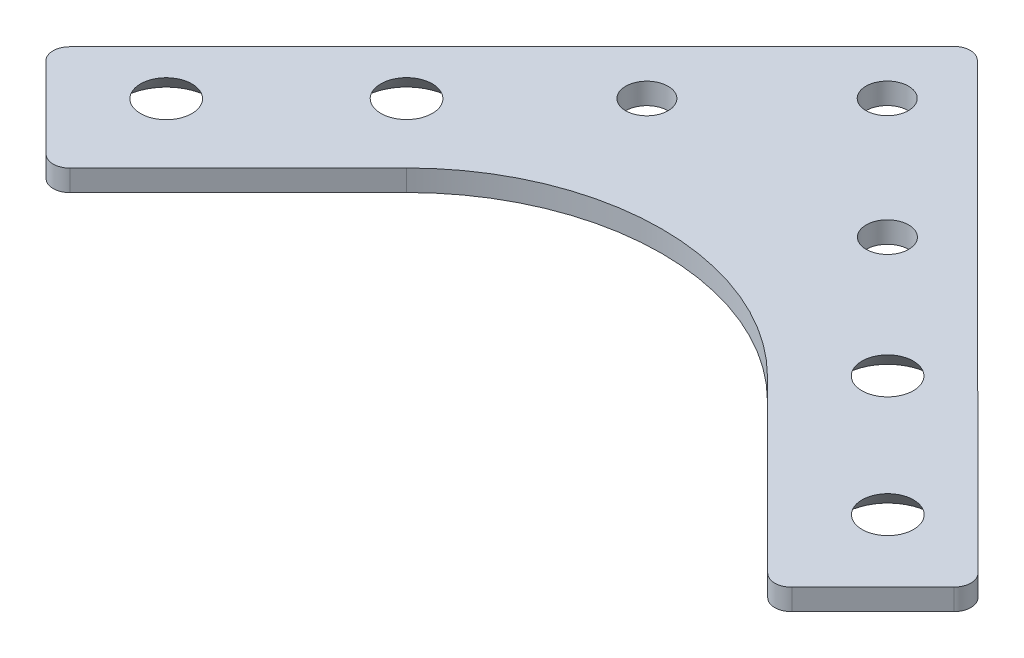
SolidWorks part; units mm, degrees
material "6061 Alloy"
ref_plane "Front Plane" through (0, 0, 0) normal (0, 0, 1) x (1, 0, 0)
ref_plane "Top Plane" through (0, 0, 0) normal (0, 1, 0) x (1, 0, 0)
ref_plane "Right Plane" through (0, 0, 0) normal (1, 0, 0) x (0, 0, -1)
sketch "Outline" plane through (0, 43.8334, 0) normal (0, -1, 0) x (1, 0, 0)
  line L0 (175.1714, -660.3981) -> (172.9281, -658.1513)
  line L1 (175.1714, -660.3981) -> (-309.3782, -175.0804) construction
  line L2 (172.9281, -658.1513) -> (175.175, -655.908)
  line L3 (176.9724, -654.1133) -> (243.4309, -587.7601)
  line L7 (227.7279, -572.0322) -> (202.162, -597.5577)
  line L8 (193.1461, -642.4518) -> (-291.4035, -157.1341) construction
  line L9 (148.2804, -597.515) -> (123.1556, -572.3504)
  line L12 (107.4278, -588.0534) -> (173.3803, -654.1105)
  line L16 (107.4306, -584.4613) -> (119.5635, -572.3475)
  line L18 (243.4337, -584.168) -> (231.32, -572.035)
  arc A0 (202.162, -597.5577) -> (148.2804, -597.515) centre (175.2425, -570.5956) cw
  arc A3 (176.9724, -654.1133) -> (173.3803, -654.1105) centre (175.1778, -652.3159) cw
  arc A4 (107.4306, -584.4613) -> (107.4278, -588.0534) centre (109.2252, -586.2587) ccw
  arc A5 (119.5635, -572.3475) -> (123.1556, -572.3504) centre (121.3582, -574.145) cw
  arc A6 (231.32, -572.035) -> (227.7279, -572.0322) centre (229.5225, -573.8296) ccw
  arc A7 (243.4337, -584.168) -> (243.4309, -587.7601) centre (241.6363, -585.9626) cw
  point P7 (0, 0)
  point P21 (175.1999, -624.4771)
  dimension "D1" = 38.1
  dimension "D2" = 2.54
  dimension "D3" = 2.54
  dimension "D4" = 2.54
  dimension "D5" = 2.54
  dimension "D6" = 2.54
extrude "Boss-Extrude1" add sketch "Outline" along normal blind 3.175 contours L3 A7 L18 A6 L7 A0 L9 A5 L16 A4 L12 A3
sketch "Hole Locations" plane through (0, 40.6584, 0) normal (0, -1, 0) x (1, 0, 0)
  line L0 (175.1856, -642.4376) -> (157.2394, -624.4629)
  line L1 (157.2394, -624.4629) -> (139.2931, -606.4881)
  line L2 (139.2931, -606.4881) -> (121.3468, -588.5134)
  line L5 (193.1604, -624.4913) -> (211.1351, -606.545)
  line L6 (211.1351, -606.545) -> (229.1098, -588.5987)
hole_wizard "1/4 (0.25) Diameter Hole1" positions "Sketch6" profile "Sketch7" hole size "1/4" standard "ANSI Inch" end condition through all
sketch "Sketch6" plane through (0, 40.6584, 0) normal (0, -1, 0) x (-1, 0, 0)
  point P0 (-175.1856, 642.4376)
  point P3 (-193.1604, 624.4913)
  point P6 (-157.2394, 624.4629)
sketch "Sketch7" plane through (175.1856, 40.6584, -642.4376) normal (1, 0, 0) x (0, 0, -1)
  line L0 (0, 0) -> (0, 3.175)
  line L1 (0, 3.175) -> (3.175, 3.175)
  line L2 (3.175, 3.175) -> (3.175, 0)
  line L5 (3.175, 0) -> (0, 0)
  line L11 (0, -6.35) -> (0, 107.95) construction
  dimension "Thru Hole Dia." = 6.35
  dimension "Thru Hole Depth" = 3.175
hole_wizard "1/4 (0.25) Diameter Hole3" positions "Sketch10" profile "Sketch11" hole size "1/4" standard "ANSI Inch" end condition through all
sketch "Sketch10" plane through (0, 40.6584, 0) normal (0, -1, 0) x (-1, 0, 0)
  point P0 (-139.2931, 606.4881)
  point P3 (-121.3468, 588.5134)
  point P6 (-211.1351, 606.545)
  point P9 (-229.1098, 588.5987)
sketch "Sketch11" plane through (139.2931, 40.6584, -606.4881) normal (1, 0, 0) x (0, 0, -1)
  line L0 (0, 0) -> (0, 3.175)
  line L1 (0, 3.175) -> (3.175, 3.175)
  line L2 (3.175, 3.175) -> (3.175, 3.9446)
  line L3 (3.175, 3.9446) -> (6.604, 0)
  line L5 (6.604, 0) -> (0, 0)
  line L6 (-3.175, 3.9446) -> (-6.604, 0) construction
  line L11 (0, -6.35) -> (0, 107.95) construction
  dimension "Thru Hole Dia." = 6.35
  dimension "Thru Hole Depth" = 3.175
  dimension "Near C'Sink Dia." = 13.208
  dimension "Near C'Sink Angle" = 82
